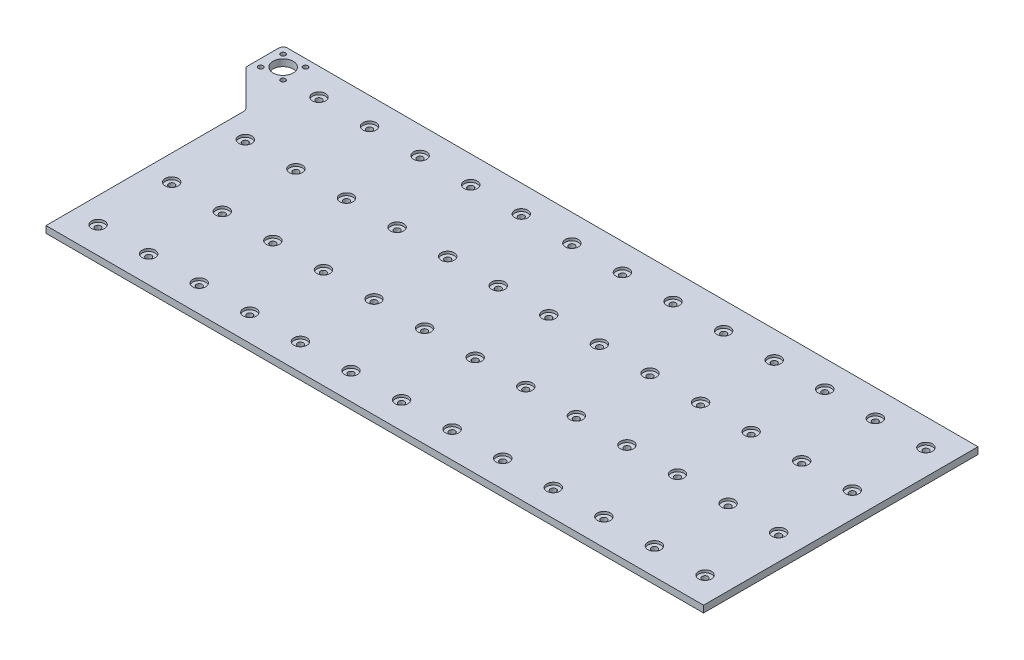
SolidWorks part; units mm, degrees
ref_plane "Front Plane" through (0, 0, 0) normal (0, 0, 1) x (1, 0, 0)
ref_plane "Top Plane" through (0, 0, 0) normal (0, 1, 0) x (1, 0, 0)
ref_plane "Right Plane" through (0, 0, 0) normal (1, 0, 0) x (0, 0, -1)
sketch "Sketch1" plane through (0, 0, 0) normal (0, 1, 0) x (1, 0, 0)
  line L0 (-35, 222.2) -> (0, 187.2)
  line L1 (0, 0) -> (616.2, 0)
  line L2 (0, 0) -> (0, 187.2)
  line L3 (0, 257.2) -> (616.2, 257.2)
  line L4 (616.2, 0) -> (616.2, 257.2)
  line L5 (0, 257.2) -> (-35, 257.2)
  line L8 (-35, 257.2) -> (-35, 222.2)
  circle A0 centre (-28, 229.2) radius 2.25
  circle A1 centre (-7, 229.2) radius 2.25
  circle A2 centre (-7, 250.2) radius 2.25
  circle A3 centre (-28, 250.2) radius 2.25
  circle A4 centre (-17.5, 239.7) radius 9.5
  dimension "D6" = 19
  dimension "D7" = 4.5
  dimension "D1" = 257.2
  dimension "D2" = 616.2
  dimension "D3" = 35
  dimension "D4" = 35
  dimension "D5" = 45
  dimension "D8" = 17.5
  dimension "D9" = 17.5
extrude "Boss-Extrude1" add sketch "Sketch1" along normal blind 6.35
fillet "Fillet1" radius 4 3 edges at (-35, 3.175, -257.2) (-35, 3.175, -222.2) (0, 3.175, -187.2)
hole_wizard "Hole1" positions "Sketch3" profile "Sketch4" legacy end condition through all
sketch "Sketch3" plane through (0, 6.35, 0) normal (0, 1, 0) x (1, 0, 0)
  line L0 (0, 185.5431) -> (0, 0) construction
  line L1 (0, 0) -> (616.2, 0) construction
  point P0 (23.7, 25.1)
  dimension "D1" = 23.7
  dimension "D2" = 25.1
sketch "Sketch4" plane through (23.7, 6.35, -25.1) normal (1, 0, 0) x (0, 0, 1)
  line L0 (0, 0) -> (0, 6.35)
  line L1 (0, 6.35) -> (2.75, 6.35)
  line L3 (2.75, 6.35) -> (2.75, 2.3812)
  line L4 (2.75, 2.3812) -> (6.12, 2.3812)
  line L5 (6.12, 2.3812) -> (6.12, 0)
  line L7 (6.12, 0) -> (0, 0)
  line L11 (0, -6.35) -> (0, 107.95) construction
  dimension "Thru Hole Dia." = 5.5
  dimension "Thru Hole Depth" = 6.35
  dimension "C'Bore Dia." = 12.24
  dimension "C'Bore Depth" = 2.3812
pattern_linear "LPattern1" count 13 spacing 47.4 along (1, 0, 0) count 4 spacing 69 along (0, 0, -1) of "Hole1"
